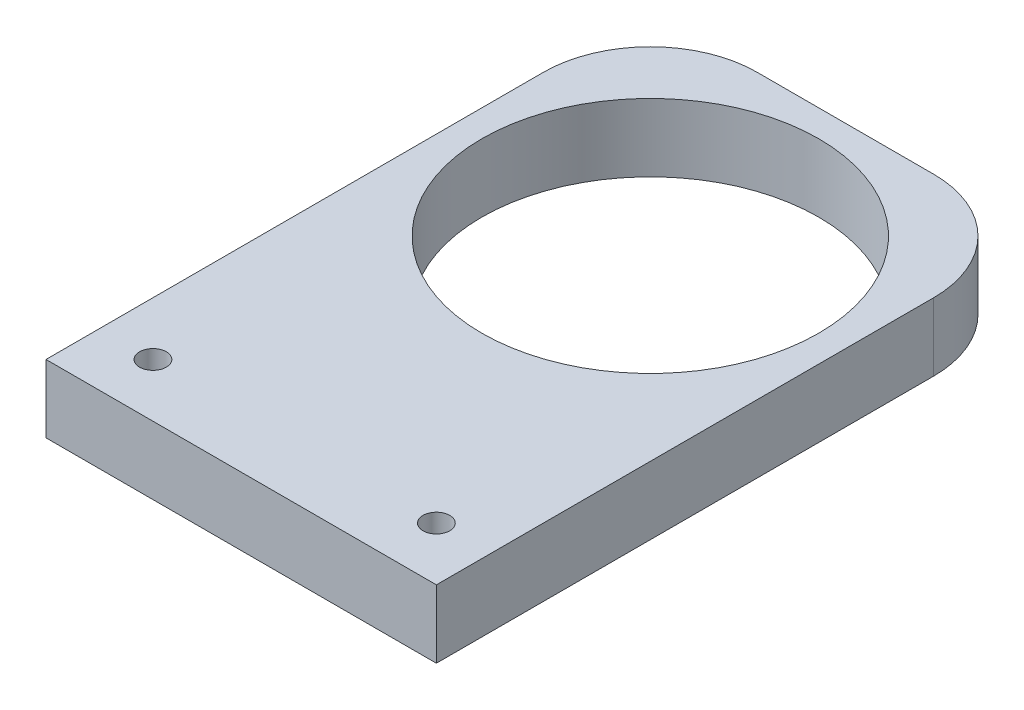
SolidWorks part; units mm, degrees
ref_plane "Front Plane" through (0, 0, 0) normal (0, 0, 1) x (1, 0, 0)
ref_plane "Top Plane" through (0, 0, 0) normal (0, 1, 0) x (1, 0, 0)
ref_plane "Right Plane" through (0, 0, 0) normal (1, 0, 0) x (0, 0, -1)
other "Default"
sketch "Sketch2" plane through (0, 0, 0) normal (0, 1, 0) x (1, 0, 0)
  line L1 (-36.5, -36.5) -> (36.5, -36.5)
  line L2 (-36.5, -36.5) -> (-36.5, 36.5)
  line L3 (-36.5, 36.5) -> (36.5, 36.5)
  line L4 (36.5, -36.5) -> (36.5, 36.5)
  line L5 (-36.5, -36.5) -> (36.5, 36.5) construction
  line L6 (-36.5, 36.5) -> (36.5, -36.5) construction
  circle A0 centre (0, 0) radius 31.5
  point P7 (0, 31.5)
  dimension "D1" = 63
  dimension "D2" = 5
extrude "Boss-Extrude2" add sketch "Sketch2" along normal mid plane 12.7
sketch "Sketch3" plane through (0, 6.35, 0) normal (0, 1, 0) x (1, 0, 0)
  line L1 (-36.5, -76.5) -> (36.5, -76.5)
  line L2 (-36.5, -76.5) -> (-36.5, -36.5)
  line L3 (-36.5, -36.5) -> (36.5, -36.5)
  line L4 (-36.5, -36.5) -> (36.5, -36.5) construction
  line L6 (36.5, -36.5) -> (36.5, -76.5)
  line L7 (36.5, -36.5) -> (36.5, 36.5) construction
  line L8 (-36.5, -66.5) -> (-26.5, -66.5) construction
  line L9 (-26.5, -66.5) -> (-26.5, -76.5) construction
  line L10 (26.5, -66.5) -> (36.5, -66.5) construction
  circle A9 centre (-26.5, -66.5) radius 2.5
  circle A10 centre (26.5, -66.5) radius 2.5
  point P6 (0, -76.5)
  dimension "D3" = 10
  dimension "D1" = 5
  dimension "D2" = 40
extrude "Bottom Mount" add sketch "Sketch3" against normal through all
sketch "Sketch1" plane through (0, 0, 0) normal (0, 1, 0) x (1, 0, 0)
  line L0 (-60, -26.5) -> (-60, 26.5) construction
  line L1 (60, 26.5) -> (60, -26.5) construction
  line L2 (60, 0) -> (-60, 0) construction
  line L3 (-70, -26.5) -> (-60, -26.5) construction
  line L4 (-70, -36.5) -> (70, -36.5) construction
  line L5 (-70, -36.5) -> (-70, 36.5)
  line L6 (-70, 36.5) -> (70, 36.5) construction
  line L7 (70, -36.5) -> (70, 36.5)
  line L8 (-70, -36.5) -> (70, 36.5) construction
  line L9 (-70, 36.5) -> (70, -36.5) construction
  line L10 (-60, -26.5) -> (-60, -36.5) construction
  line L11 (36.5, 36.5) -> (-36.5, 36.5) construction
  line L12 (-70, 36.5) -> (-36.5, 36.5)
  line L13 (-36.5, 36.5) -> (-36.5, -36.5)
  line L14 (-36.5, -36.5) -> (-70, -36.5)
  line L15 (70, -36.5) -> (36.5, -36.5)
  line L16 (36.5, -36.5) -> (36.5, 36.5)
  line L17 (36.5, 36.5) -> (70, 36.5)
  circle A1 centre (-60, -26.5) radius 2.5
  circle A2 centre (-60, 26.5) radius 2.5
  circle A3 centre (60, 26.5) radius 2.5
  circle A4 centre (60, -26.5) radius 2.5
  point P1 (0, 0)
  dimension "D3" = 5
  dimension "D2" = 120
  dimension "D5" = 10
extrude "Side Mounts" [suppressed] add sketch "Sketch1" along normal mid plane 12.7
fillet "Bottom Mount Fillets" radius 20 2 edges at (-36.5, 0, -36.5) (36.5, 0, -36.5)
